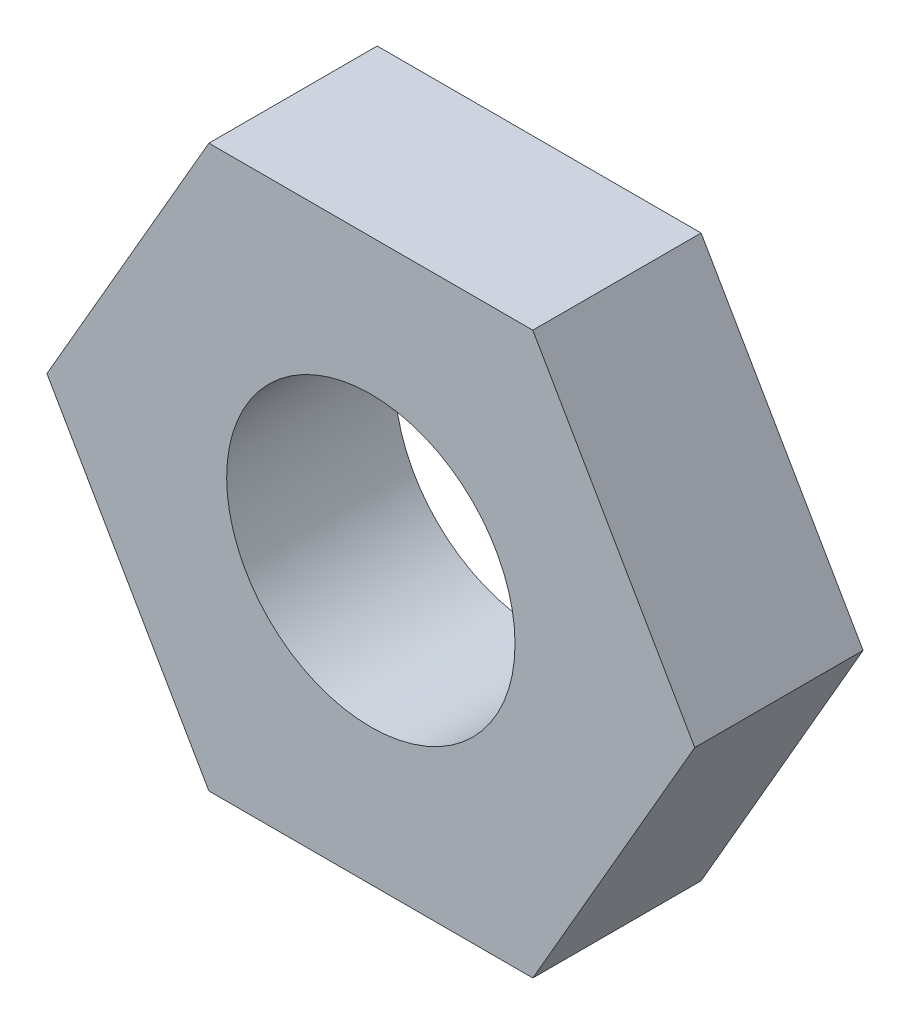
SolidWorks part; units mm, degrees
ref_plane "Front Plane" through (0, 0, 0) normal (1, 0, 0) x (0, 1, 0)
ref_plane "Top Plane" through (0, 0, 0) normal (0, 0, 1) x (0, 1, 0)
ref_plane "Right Plane" through (0, 0, 0) normal (0, 1, 0) x (-1, 0, 0)
sketch "Sketch1" plane through (0, 0, 0) normal (0, 0, 1) x (0, 1, 0)
  line L1 (0, -7.3323) -> (6.35, -3.6662)
  line L2 (6.35, -3.6662) -> (6.35, 3.6662)
  line L3 (6.35, 3.6662) -> (0, 7.3323)
  line L4 (0, 7.3323) -> (-6.35, 3.6662)
  line L5 (-6.35, 3.6662) -> (-6.35, -3.6662)
  line L6 (-6.35, -3.6662) -> (0, -7.3323)
  circle A0 centre (0, 0) radius 6.35 construction
  dimension "D1" = 12.7
extrude "Boss-Extrude1" add sketch "Sketch1" along normal blind 3.81
hole_wizard "Tap Drill for 5/16-18 Tap1" positions "Sketch2" profile "Sketch3" hole size "5/16-18" standard "ANSI Inch"
sketch "Sketch2" plane through (0, 0, 3.81) normal (0, 0, 1) x (1, 0, 0)
  point P0 (0, 0)
sketch "Sketch3" plane through (0, 0, 3.81) normal (1, 0, 0) x (0, -1, 0)
  line L0 (0, 0) -> (0, 27.3611)
  line L1 (0, 27.3611) -> (3.2639, 25.4)
  line L2 (3.2639, 25.4) -> (3.2639, 0)
  line L5 (3.2639, 0) -> (0, 0)
  line L10 (0, 27.3611) -> (-3.2639, 25.4) construction
  line L11 (0, -6.35) -> (0, 107.95) construction
  dimension "Hole Dia." = 6.5278
  dimension "Hole Depth" = 25.4
  dimension "Drill Angle" = 118
